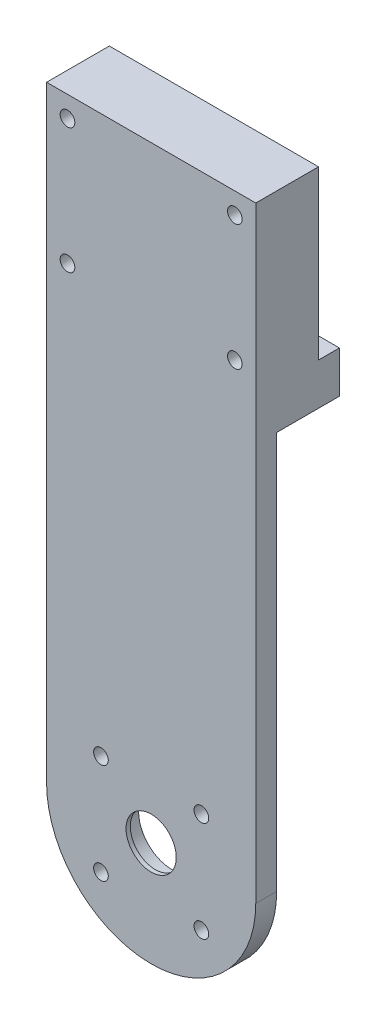
SolidWorks part; units mm, degrees
ref_plane "Front Plane" through (0, 0, 0) normal (0, 0, 1) x (1, 0, 0)
ref_plane "Top Plane" through (0, 0, 0) normal (0, 1, 0) x (1, 0, 0)
ref_plane "Right Plane" through (0, 0, 0) normal (1, 0, 0) x (0, 0, -1)
sketch "Sketch1" plane through (0, 0, 0) normal (0, 0, 1) x (1, 0, 0)
  line L2 (-25, 0) -> (-25, 25)
  line L3 (-25, 25) -> (25, 25)
  line L4 (25, 0) -> (25, 25)
  arc A0 (-25, 0) -> (25, 0) centre (0, 0) ccw
  dimension "D1" = 25
  dimension "D2" = 50
  dimension "D3" = 25
extrude "Boss-Extrude1" add sketch "Sketch1" along normal blind 5
sketch "Sketch3" plane through (0, 0, 0) normal (0, 0, -1) x (-1, 0, 0)
  circle A0 centre (0, 0) radius 6
  dimension "D1" = 12
extrude "Cut-Extrude2" cut sketch "Sketch3" against normal through all
sketch "Sketch4" plane through (0, 0, 0) normal (0, 0, -1) x (-1, 0, 0)
  circle A0 centre (0, 0) radius 8
  dimension "D1" = 16
extrude "Cut-Extrude3" cut sketch "Sketch4" against normal blind 4
sketch "Sketch5" plane through (0, 0, 0) normal (0, 0, 1) x (1, 0, 0)
  line L1 (-25, 25) -> (25, 25)
  line L2 (-25, 25) -> (-25, 145)
  line L3 (-25, 145) -> (25, 145)
  line L4 (25, 25) -> (25, 145)
  dimension "D1" = 50
  dimension "D2" = 120
extrude "Boss-Extrude2" add sketch "Sketch5" along normal blind 5 contours L2 L3 L4 L1
sketch "Sketch6" plane through (0, 0, 0) normal (0, 0, -1) x (-1, 0, 0)
  line L0 (-3.2092, 0) -> (0, 0) construction
  line L1 (0, 0) -> (0, 4.5145) construction
  circle A0 centre (-12, -12) radius 1.75
  circle A2 centre (12, -12) radius 1.75
  circle A3 centre (12, 12) radius 1.75
  circle A4 centre (-12, 12) radius 1.75
  dimension "D1" = 3.5
  dimension "D2" = 12
  dimension "D3" = 12
extrude "Cut-Extrude4" cut sketch "Sketch6" against normal through all
sketch "Sketch7" plane through (0, 0, 0) normal (0, 0, -1) x (-1, 0, 0)
  line L0 (-3.2118, 0) -> (0, 0) construction
  line L1 (-8.7091, -12) -> (-10.3546, -9.15)
  line L2 (-10.3546, -9.15) -> (-13.6454, -9.15)
  line L3 (-13.6454, -9.15) -> (-15.2909, -12)
  line L4 (-15.2909, -12) -> (-13.6454, -14.85)
  line L5 (-13.6454, -14.85) -> (-10.3546, -14.85)
  line L6 (-10.3546, -14.85) -> (-8.7091, -12)
  line L7 (0, 0) -> (0, 3.2224) construction
  line L8 (10.3546, -14.85) -> (8.7091, -12)
  line L9 (13.6454, -14.85) -> (10.3546, -14.85)
  line L10 (15.2909, -12) -> (13.6454, -14.85)
  line L11 (13.6454, -9.15) -> (15.2909, -12)
  line L12 (10.3546, -9.15) -> (13.6454, -9.15)
  line L13 (8.7091, -12) -> (10.3546, -9.15)
  line L14 (8.7091, 12) -> (10.3546, 9.15)
  line L15 (10.3546, 9.15) -> (13.6454, 9.15)
  line L16 (13.6454, 9.15) -> (15.2909, 12)
  line L17 (15.2909, 12) -> (13.6454, 14.85)
  line L18 (13.6454, 14.85) -> (10.3546, 14.85)
  line L19 (10.3546, 14.85) -> (8.7091, 12)
  line L20 (-10.3546, 14.85) -> (-8.7091, 12)
  line L21 (-13.6454, 14.85) -> (-10.3546, 14.85)
  line L22 (-15.2909, 12) -> (-13.6454, 14.85)
  line L23 (-13.6454, 9.15) -> (-15.2909, 12)
  line L24 (-10.3546, 9.15) -> (-13.6454, 9.15)
  line L25 (-8.7091, 12) -> (-10.3546, 9.15)
  circle A0 centre (-12, -12) radius 2.85 construction
  circle A1 centre (12, -12) radius 2.85 construction
  circle A2 centre (12, 12) radius 2.85 construction
  circle A3 centre (-12, 12) radius 2.85 construction
  dimension "D1" = 5.7
extrude "Cut-Extrude5" cut sketch "Sketch7" against normal blind 2
sketch "Sketch9" plane through (0, 0, 0) normal (0, 0, -1) x (-1, 0, 0)
  line L0 (25, 145) -> (25, 0) construction
  line L1 (-25, 145) -> (25, 145)
  line L2 (-25, 145) -> (-25, 105)
  line L3 (-25, 105) -> (25, 105)
  line L4 (25, 145) -> (25, 105)
  dimension "D1" = 40
extrude "Boss-Extrude3" add sketch "Sketch9" along normal blind 10
sketch "Sketch10" plane through (0, 0, 0) normal (0, 0, -1) x (-1, 0, 0)
  line L0 (25, 105) -> (25, 0) construction
  line L1 (-25, 105) -> (25, 105)
  line L2 (-25, 105) -> (-25, 95)
  line L3 (-25, 95) -> (25, 95)
  line L4 (25, 105) -> (25, 95)
  dimension "D1" = 10
extrude "Boss-Extrude4" add sketch "Sketch10" along normal blind 15
sketch "Sketch11" plane through (0, 0, -10) normal (0, 0, -1) x (-1, 0, 0)
  line L0 (25, 145) -> (-25, 145) construction
  line L2 (-25, 145) -> (-25, 105) construction
  line L3 (0, 120.6398) -> (0, 131.6386) construction
  line L4 (25, 125) -> (12.3237, 125) construction
  line L5 (25, 105) -> (25, 145) construction
  circle A0 centre (-20, 140) radius 1.75
  circle A1 centre (20, 140) radius 1.75
  circle A2 centre (20, 110) radius 1.75
  circle A3 centre (-20, 110) radius 1.75
  dimension "D1" = 3.5
  dimension "D2" = 5
  dimension "D3" = 5
extrude "Cut-Extrude6" cut sketch "Sketch11" against normal through all
